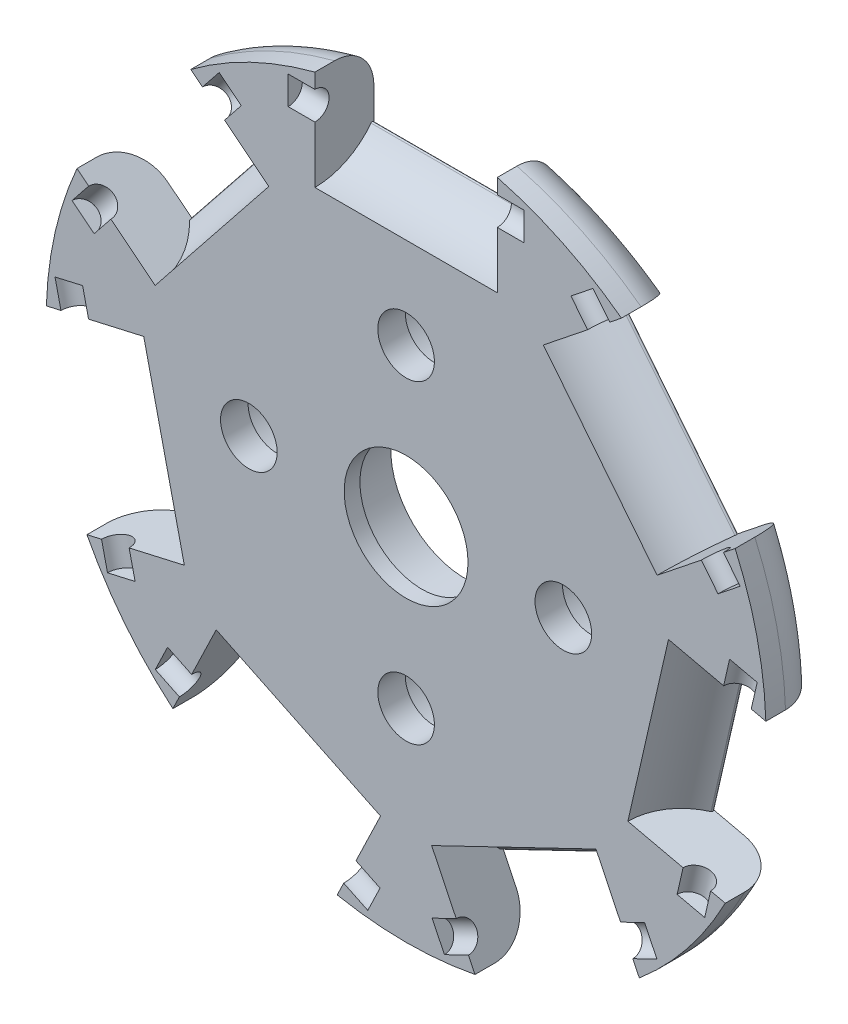
SolidWorks part; units mm, degrees
other "Markup1"
sketch "Sketch8" plane through (32.7336, 32.7336, 0) normal (0.5701, 0.1846, 0.8006) x (0.8043, 0.0736, -0.5897)
ref_plane "Front Plane" through (0, 0, 0) normal (0, 0, 1) x (1, 0, 0)
ref_plane "Top Plane" through (0, 0, 0) normal (0, 1, 0) x (1, 0, 0)
ref_plane "Right Plane" through (0, 0, 0) normal (1, 0, 0) x (0, 0, -1)
sketch "Sketch1" plane through (0, 0, 0) normal (0, 0, 1) x (1, 0, 0)
  circle A0 centre (0, 0) radius 29.0703
  dimension "D1" = 58.1406
extrude "Boss-Extrude2" add sketch "Sketch1" against normal blind 4.7625
fillet "Fillet1" radius 3.175 1 edges at (29.0703, 0, -4.7625)
sketch "Sketch2" plane through (0, 0, 0) normal (0, 0, 1) x (1, 0, 0)
  line L1 (-12.7, 29.0703) -> (12.7, 29.0703) construction
  line L2 (-7.366, 30.3403) -> (7.366, 30.3403)
  line L3 (-7.366, 30.3403) -> (-7.366, 19.9263)
  line L4 (-7.366, 19.9263) -> (7.366, 19.9263)
  line L5 (7.366, 30.3403) -> (7.366, 19.9263)
  line L6 (-7.366, 30.3403) -> (7.366, 19.9263) construction
  line L7 (-7.366, 19.9263) -> (7.366, 30.3403) construction
  line L35 (0, 0) -> (0, 29.0703) construction
  circle A1 centre (0, 0) radius 29.0703 construction
  point P10 (0, 25.1333)
  circle M7 centre (0, 0) radius 29.0703
  dimension "D1" = 14.732
  dimension "D2" = 10.414
  dimension "D3" = 1.27
  dimension "D4" = 25.4
extrude "Cut-Extrude2" cut sketch "Sketch2" against normal blind 12.7 contours L5 L3 L4 M7
pattern_circular "CirPattern1" count 7 over 360 about axis through (0, 0, 0) along (0, 0, 1) of "Cut-Extrude2"
ref_plane "Plane1" through (0, 0, 0) normal (1, 0, 0) x (0, 0, -1)
sketch "Sketch4" plane through (0, 0, 0) normal (1, 0, 0) x (0, 0, -1)
  line L0 (4.7625, 19.9263) -> (0, 19.9263) construction
  circle A0 centre (0, 25.7683) radius 1.143
  dimension "D1" = 2.286
  dimension "D2" = 5.842
extrude "Cut-Extrude4" cut sketch "Sketch4" against normal mid plane 19.05
pattern_circular "CirPattern2" count 7 over 360 about axis through (0, 0, 0) along (0, 0, 1) of "Cut-Extrude4"
sketch "Sketch5" plane through (0, 0, 0) normal (0, 0, 1) x (1, 0, 0)
  circle A0 centre (0, 0) radius 6
  point P0 (0, 0)
  dimension "D2" = 12
sketch "Sketch6" plane through (0, 0, -4.7625) normal (0, 0, -1) x (-1, 0, 0)
  circle A1 centre (12.7, 0) radius 2.286
  circle A4 centre (0, -12.7) radius 2.286
  circle A5 centre (-12.7, 0) radius 2.286
  circle A6 centre (0, 12.7) radius 2.286
  point P12 (0, 0)
  dimension "D4" = 4.572
  dimension "D1" = 12.7
  dimension "D2" = 4
extrude "Cut-Extrude7" cut sketch "Sketch6" against normal through all
sketch "Sketch7" plane through (0, 0, -4.7625) normal (0, 0, -1) x (-1, 0, 0)
  circle A1 centre (12.7, 0) radius 4.445
  circle A4 centre (0, -12.7) radius 4.445
  circle A5 centre (-12.7, 0) radius 4.445
  circle A6 centre (0, 12.7) radius 4.445
  point P15 (0, 0)
  dimension "D1" = 4
  dimension "D2" = 8.89
extrude "Cut-Extrude8" cut sketch "Sketch7" against normal blind 2.54
sketch "Sketch10" plane through (7.366, 0, 0) normal (-1, 0, 0) x (0, 0, 1)
  line L0 (-4.7625, 24.8256) -> (-4.7625, 19.9263) construction
  line L1 (-4.7625, 19.9263) -> (0, 19.9263)
  line L2 (-4.7625, 19.9263) -> (-4.7625, 22.6092)
  line L4 (0, 19.9263) -> (0, 20.0533)
  arc A0 (-4.7625, 22.6092) -> (0, 20.0533) centre (0, 25.7683) ccw
  dimension "D1" = 11.43
  dimension "D2" = 4.7625
extrude "Boss-Extrude4" add sketch "Sketch10" along normal up to next
fillet "Fillet2" radius 0.127 1 edges at (0, 22.6092, -4.7625)
pattern_circular "CirPattern5" count 7 over 360 of "Boss-Extrude4", "Fillet2"
extrude "Cut-Extrude9" cut sketch "Sketch5" against normal blind 5.08 contours A0
sketch "Sketch11" plane through (0, 0, 0) normal (0, 0, 1) x (1, 0, 0)
  circle A0 centre (0, 0) radius 5
  circle A1 centre (0, 0) radius 6 construction
  circle A2 centre (0, 0) radius 6
  dimension "D1" = 10
extrude "Boss-Extrude5" add sketch "Sketch11" against normal blind 1.27
